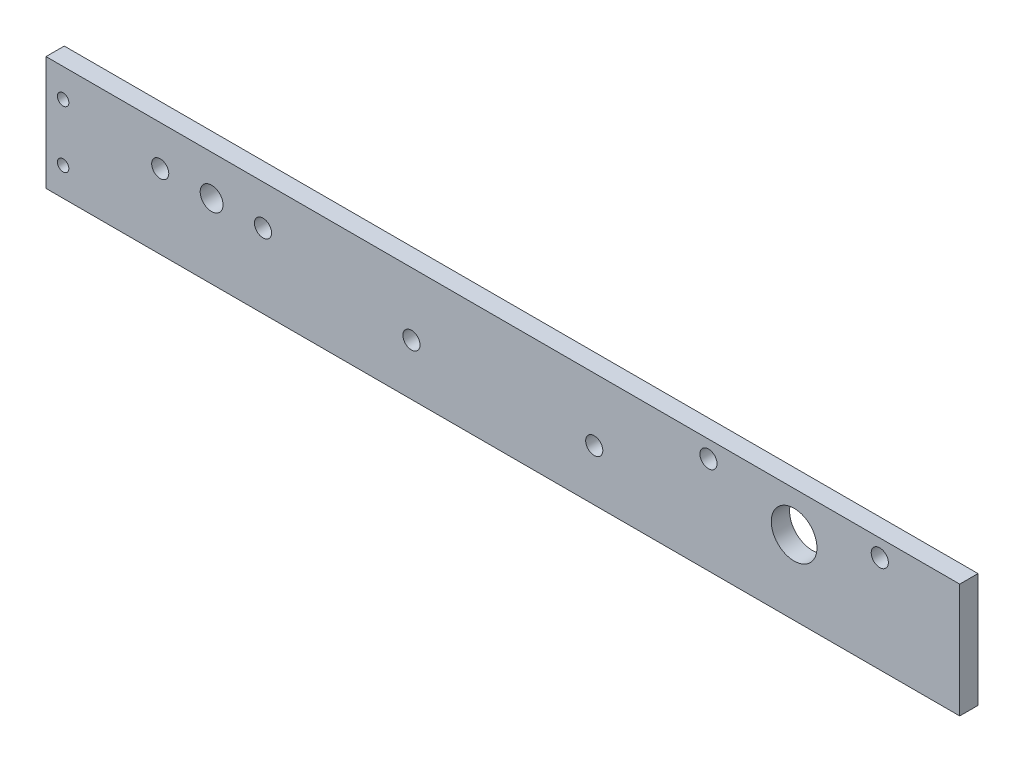
SolidWorks part; units mm, degrees
material "Balsa"
ref_plane "Front Plane" through (0, 0, 0) normal (0, 0, 1) x (1, 0, 0)
ref_plane "Top Plane" through (0, 0, 0) normal (0, 1, 0) x (1, 0, 0)
ref_plane "Right Plane" through (0, 0, 0) normal (1, 0, 0) x (0, 0, -1)
ref_plane "Plane1" through (0, 0, 10) normal (0, 0, 1) x (1, 0, 0)
sketch "Sketch2" plane through (0, -10, 10) normal (0, 0, -1) x (1, 0, 0)
  line L1 (0, -10) -> (160, -10)
  line L2 (0, -10) -> (0, 10)
  line L3 (0, 10) -> (160, 10)
  line L4 (160, -10) -> (160, 10)
  dimension "D1" = 20
  dimension "D2" = 160
extrude "Boss-Extrude1" add sketch "Sketch2" along normal blind 3.2
sketch "Sketch4" plane through (0, 0, 0) normal (0, 1, 0) x (1, 0, 0)
  line L0 (0, -10) -> (160, -10) construction
  line L1 (0, -6.8) -> (80, -6.8)
  line L2 (0, -6.8) -> (0, -10)
  line L3 (0, -10) -> (80, -10)
  line L4 (80, -6.8) -> (80, -10)
  line L5 (160, -6.8) -> (160, -10) construction
  dimension "D1" = 80
  dimension "D2" = 80
sketch "Sketch5" plane through (0, 0, 10) normal (0, 0, 1) x (1, 0, 0)
  line L0 (102, 2.15) -> (102, -20)
  line L1 (102, 0) -> (102, 4.3) construction
  line L2 (160, -20) -> (0, -20) construction
  line L3 (58, 2.15) -> (58, -20)
  line L4 (58, 0) -> (58, 4.3) construction
  line L7 (29, -7) -> (131, -7)
  line L9 (0, 0) -> (160, 0) construction
  circle A0 centre (131, -7) radius 4
  circle A1 centre (29, -7) radius 2
  point P12 (0, 0)
  dimension "D1" = 7
  dimension "D2" = 8
extrude "Cut-Extrude1" cut sketch "Sketch5" against normal through all both and the other way through all contours A0 | A1
sketch "Sketch6" plane through (0, 0, 10) normal (0, 0, 1) x (1, 0, 0)
  circle A0 centre (96, -11) radius 1.5
  circle A1 centre (64, -11) radius 1.5
  dimension "D1" = 32
extrude "Cut-Extrude2" cut sketch "Sketch6" against normal blind 10
sketch "Sketch7" plane through (0, 0, 10) normal (0, 0, 1) x (1, 0, 0)
  circle A0 centre (3, -15) radius 1
  circle A1 centre (3, -5) radius 1
  dimension "D1" = 2
extrude "Cut-Extrude3" cut sketch "Sketch7" against normal through all both and the other way through all
sketch "Sketch8" plane through (0, 0, 10) normal (0, 0, 1) x (1, 0, 0)
  circle A0 centre (146, -3) radius 1.5 construction
  circle A1 centre (146, -3) radius 1.5
  circle A2 centre (116, -3) radius 1.5 construction
  circle A3 centre (116, -3) radius 1.5
extrude "Cut-Extrude4" cut sketch "Sketch8" against normal blind 10
sketch "Sketch9" plane through (0, 0, 6.8) normal (0, 0, -1) x (-1, 0, 0)
  circle A0 centre (-20, -7) radius 1.5
  circle A1 centre (-38, -7) radius 1.5
extrude "Cut-Extrude5" cut sketch "Sketch9" against normal blind 10
